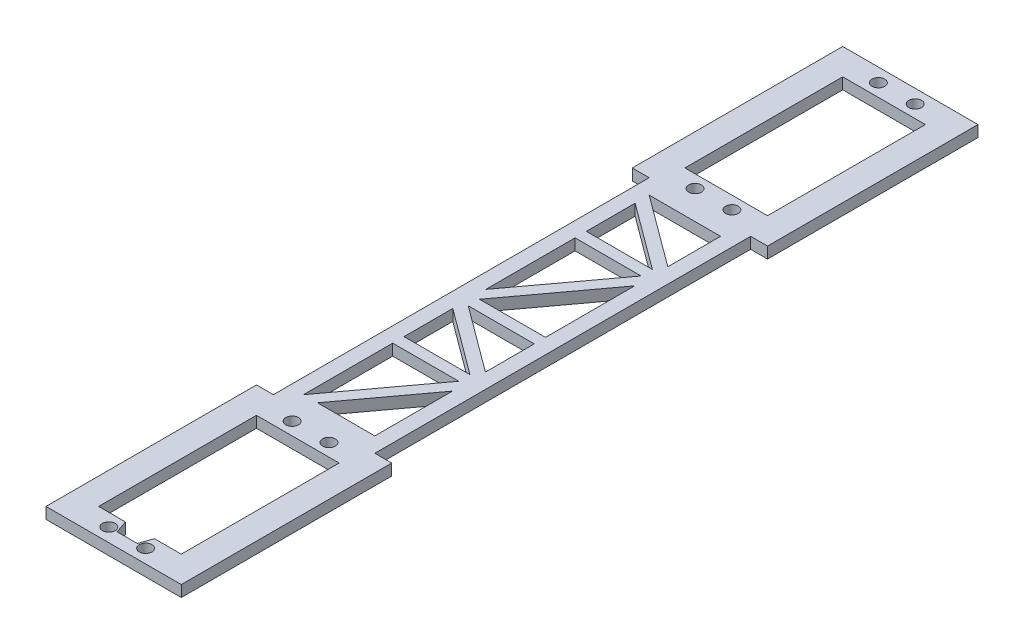
SolidWorks part; units mm, degrees
ref_plane "Front Plane" through (0, 0, 0) normal (0, 0, 1) x (1, 0, 0)
ref_plane "Top Plane" through (0, 0, 0) normal (0, 1, 0) x (1, 0, 0)
ref_plane "Right Plane" through (0, 0, 0) normal (1, 0, 0) x (0, 0, -1)
sketch "Sketch1" plane through (0, 0, 0) normal (0, 1, 0) x (1, 0, 0)
  line L0 (-18, 28) -> (18, 28)
  line L1 (-11, 21) -> (11, 21)
  line L2 (-11, 21) -> (-11, -21)
  line L3 (-11, -21) -> (11, -21)
  line L4 (11, 21) -> (11, -21)
  line L5 (-11, 21) -> (11, -21) construction
  line L6 (-11, -21) -> (11, 21) construction
  line L7 (18, 28) -> (18, -28)
  line L8 (-5.8215, -21) -> (5.8215, -21)
  line L9 (-18, -28) -> (18, -28)
  line L10 (-18, 28) -> (-18, -28)
  line L11 (-4.9, -21) -> (-4.9, -24.3895)
  line L12 (0, -23.2952) -> (-4.9, -23.2952)
  line L13 (0, -21) -> (0, -23.2952)
  line L14 (0, -28) -> (0, -128)
  line L15 (4.9, -21) -> (4.9, -24.3895)
  line L16 (-4.9, 21) -> (-4.9, 24.3895)
  line L17 (4.9, 21) -> (4.9, 24.3895)
  line L18 (-4.9, -135) -> (-4.9, -131.61)
  line L19 (-13.5, -28) -> (13.5, -28)
  line L20 (-13.5, -28) -> (-13.5, -128)
  line L21 (-13.5, -128) -> (13.5, -128)
  line L22 (13.5, -28) -> (13.5, -128)
  line L23 (-13.5, -28) -> (13.5, -128) construction
  line L24 (-13.5, -128) -> (13.5, -28) construction
  line L25 (-18, -128) -> (18, -128)
  line L26 (18, -184) -> (18, -128)
  line L27 (-18, -184) -> (-18, -128)
  line L28 (-18, -184) -> (18, -184)
  line L29 (0, -177) -> (0, -180.0637)
  line L34 (0, -180.0637) -> (-4.9, -180.0637)
  line L35 (-11, -135) -> (11, -135)
  line L36 (-11, -135) -> (-11, -177)
  line L37 (-11, -177) -> (11, -177)
  line L38 (11, -135) -> (11, -177)
  line L39 (-11, -135) -> (11, -177) construction
  line L40 (-11, -177) -> (11, -135) construction
  line L41 (-4.9, -177) -> (-4.9, -180.39)
  line L42 (4.9, -177) -> (4.9, -180.39)
  line L43 (-6.3676, -156) -> (7.6606, -156)
  line L44 (4.9, -135) -> (4.9, -131.61)
  line L45 (-9.5, -32) -> (-9.5, -124)
  line L46 (-9.5, -124) -> (9.5, -124)
  line L47 (9.5, -32) -> (9.5, -124)
  line L48 (-9.5, -32) -> (9.5, -32)
  line L49 (-9.5, -32) -> (9.5, -46.0476)
  line L50 (-9.5, -35.7309) -> (9.5, -49.7785)
  line L51 (9.5, -49.7785) -> (-9.5, -75.4769)
  line L52 (9.5, -54.8247) -> (-9.5, -80.5231)
  line L53 (-9.5, -80.5231) -> (9.5, -94.5707)
  line L54 (-9.5, -84.254) -> (9.5, -98.3016)
  line L55 (9.5, -98.3016) -> (-9.5, -124)
  line L56 (9.5, -103.3478) -> (-5.7691, -124)
  line L57 (8.0659, -48.7182) -> (-9.5, -48.7182)
  line L58 (8.0659, -51.7182) -> (-9.5, -51.7182)
  line L59 (-8.0659, -78.5834) -> (9.5, -78.5834)
  line L60 (-8.0659, -81.5834) -> (9.5, -81.5834)
  line L61 (8.0659, -100.2413) -> (-9.5, -100.2413)
  line L62 (8.0659, -97.2413) -> (-9.5, -97.2413)
  line L63 (2.6828, -180.39) -> (3.8652, -177)
  line L64 (3.21, -180.39) -> (-3.21, -180.39)
  line L65 (-2.6828, -180.39) -> (-3.8652, -177)
  circle A0 centre (-4.9, -24.3895) radius 1.6895
  circle A1 centre (4.9, -24.3895) radius 1.6895
  circle A2 centre (-4.9, 24.3895) radius 1.6895
  circle A3 centre (4.9, 24.3895) radius 1.6895
  circle A4 centre (-4.9, -180.39) radius 1.69
  circle A5 centre (4.9, -180.39) radius 1.69
  circle A6 centre (-4.9, -131.61) radius 1.69
  circle A7 centre (4.9, -131.61) radius 1.69
  point P0 (0, 0)
  point P29 (0, -78)
  point P37 (0, -156)
  dimension "D5" = 3.379
  dimension "D13" = 3.38
  dimension "D1" = 42
  dimension "D2" = 22
  dimension "D4" = 3.3895
  dimension "D6" = 4.9
  dimension "D7" = 100
  dimension "D8" = 36
  dimension "D9" = 27
  dimension "D10" = 42
  dimension "D11" = 22
  dimension "D12" = 3.39
  dimension "D15" = 3
  dimension "D16" = 3
  dimension "D17" = 3
  dimension "D18" = 90
  dimension "D19" = 3
  dimension "D20" = 3
  dimension "D21" = 3
  dimension "D22" = 3
  dimension "D3" = 7
  dimension "D14" = 4
extrude "Boss-Extrude1" add sketch "Sketch1" along normal blind 3
